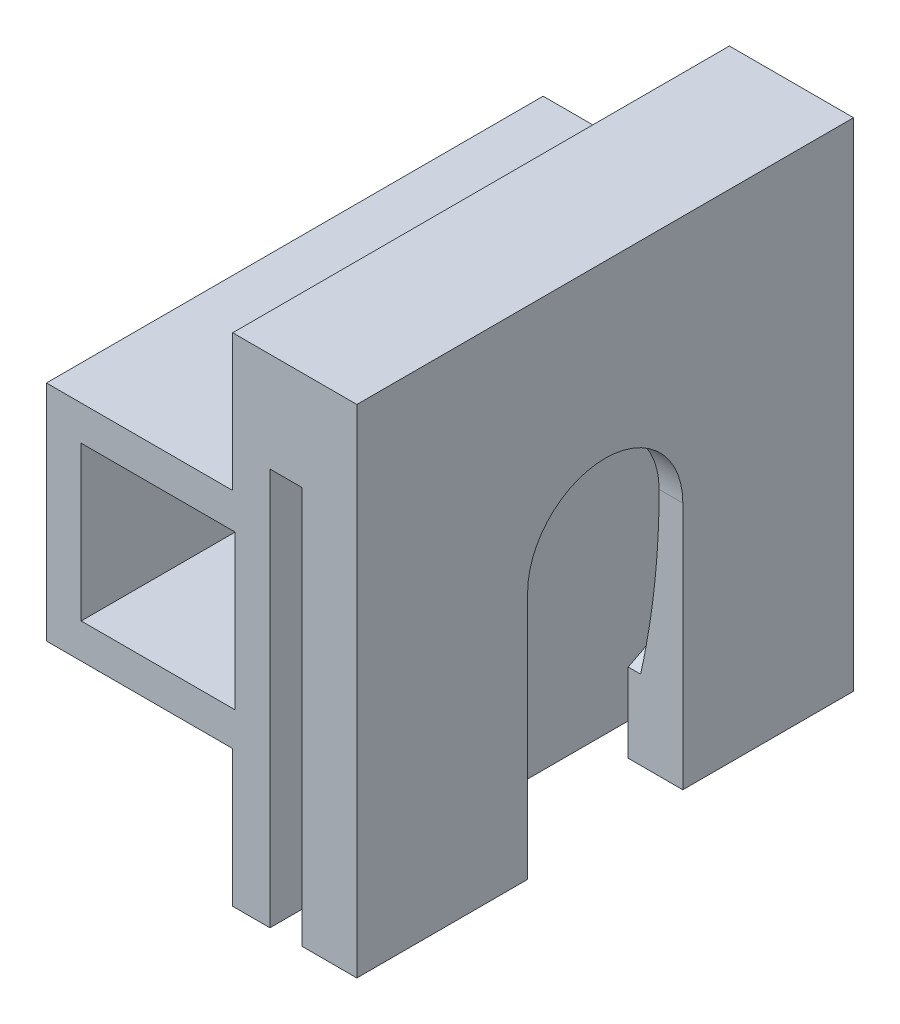
SolidWorks part; units mm, degrees
ref_plane "Plan de face" through (0, 0, 0) normal (0, 0, 1) x (1, 0, 0)
ref_plane "Plan de dessus" through (0, 0, 0) normal (0, 1, 0) x (1, 0, 0)
ref_plane "Plan de droite" through (0, 0, 0) normal (1, 0, 0) x (0, 0, -1)
sketch "Sketch1" plane through (0, 0, 0) normal (0, 0, 1) x (1, 0, 0)
  line L1 (4.5, 4.5) -> (-4.5, 4.5)
  line L2 (4.5, 4.5) -> (4.5, -4.5)
  line L3 (4.5, -4.5) -> (-4.5, -4.5)
  line L4 (-4.5, 4.5) -> (-4.5, -4.5)
  line L5 (4.5, 4.5) -> (-4.5, -4.5) construction
  line L6 (4.5, -4.5) -> (-4.5, 4.5) construction
  point P0 (0, 0)
  dimension "D1" = 9
extrude "Boss-Extrude1" add sketch "Sketch1" along normal blind 20
sketch "Sketch2" plane through (0, 0, 0) normal (0, 0, -1) x (-1, 0, 0)
  line L1 (3, 3) -> (-3, 3)
  line L2 (3, 3) -> (3, -3)
  line L3 (3, -3) -> (-3, -3)
  line L4 (-3, 3) -> (-3, -3)
  line L5 (3, 3) -> (-3, -3) construction
  line L6 (3, -3) -> (-3, 3) construction
  point P0 (0, 0)
  dimension "D1" = 6
extrude "Cut-Extrude1" cut sketch "Sketch2" against normal through all
sketch "Sketch4" plane through (4.5, 0, 0) normal (1, 0, 0) x (0, 0, -1)
  line L0 (-20, -4.5) -> (-20, 4.5) construction
  line L1 (-20, 10) -> (0, 10)
  line L2 (-20, 10) -> (-20, -10)
  line L3 (-20, -10) -> (0, -10)
  line L4 (0, 10) -> (0, -10)
  line L5 (0, -4.5) -> (0, 4.5) construction
  line L6 (-20, 10) -> (0, 4.5) construction
  line L7 (0, -4.5) -> (-20, -10) construction
extrude "Boss-Extrude2" add sketch "Sketch4" against normal up to surface (1.5 mm away) up to face at (3, 0, 10)
ref_plane "Plane1" through (4.5, 0, 0) normal (1, 0, 0) x (0, 0, -1)
ref_plane "Plane2" through (0, 0, 10) normal (0, 0, -1) x (-1, 0, 0)
ref_plane "Plane3" through (0, 0, 0) normal (0, 1, 0) x (1, 0, 0)
ref_axis "Axis1" through (88.99, 0, 10) along (-1, 0, 0)
sketch "Sketch5" plane through (4.5, 0, 0) normal (1, 0, 0) x (0, 0, -1)
  line L4 (0, -10) -> (0, 10)
  line L5 (0, -10) -> (0, 10)
  line L6 (0, 10) -> (-20, 10)
  line L7 (0, 10) -> (-20, 10)
  line L8 (-20, 10) -> (-20, -10)
  line L9 (-20, 10) -> (-20, -10)
  line L10 (-20, -10) -> (0, -10)
  line L11 (-20, -10) -> (0, -10)
  dimension "D1" = 0
extrude "Boss-Extrude3" add sketch "Sketch5" along normal blind 3.5
sketch "Sketch6" plane through (0, 0, 10) normal (0, 0, -1) x (-1, 0, 0)
  line L0 (-4.5, 7.5) -> (-4.5, 0)
  line L1 (-4.5, 0.825) -> (-4.5, -0.825) construction
  line L2 (-4.5, 7.5) -> (-6.3, 7.5)
  line L3 (-6.3, 7.5) -> (-6.3, 0) construction
  line L4 (55, 0) -> (-55, 0) construction
  line L5 (-8, 10) -> (-8, -10) construction
  line L6 (-8, 10) -> (-8, -10) construction
  line L7 (-8, 10) -> (-6.3, 7.5) construction
  line L9 (-4.5, 0) -> (-7.2003, 0)
  arc A0 (-6.3, 7.5) -> (-7.2003, 0) centre (24.49, 0) ccw
  dimension "D3" = 30.79
  dimension "D1" = 1.8
  dimension "D2" = 7.5
revolve "Cut-Revolve2" cut sketch "Sketch6" angle 360 about axis through (88.99, 0, 10) along (-1, 0, 0)
sketch "Sketch7" plane through (0, -10, 0) normal (0, -1, 0) x (1, 0, 0)
  line L0 (3, 20) -> (8, 20) construction
  line L1 (4.5, 20) -> (6.3, 20)
  line L2 (4.5, 20) -> (4.5, 0)
  line L3 (4.5, 0) -> (6.3, 0)
  line L4 (6.3, 20) -> (6.3, 0)
  line L5 (3, 0) -> (8, 0) construction
  line L6 (4.5, 2.5) -> (4.5, 17.5) construction
  line L7 (6.3, 2.5) -> (6.3, 17.5) construction
extrude "Cut-Extrude5" cut sketch "Sketch7" against normal blind 16
sketch "Sketch8" plane through (8, 0, 0) normal (1, 0, 0) x (0, 0, -1)
  line L0 (-10, 0) -> (-10, -10) construction
  line L1 (-6.875, 0) -> (-6.875, -10)
  line L2 (-13.125, 0) -> (-13.125, -10)
  line L3 (-10, -0.825) -> (-10, 0.825) construction
  line L4 (55, 0) -> (-55, 0) construction
  line L5 (-20, -10) -> (0, -10) construction
  arc A0 (-6.875, 0) -> (-13.125, 0) centre (-10, 0) ccw
  arc A1 (-13.125, -10) -> (-6.875, -10) centre (-10, -10) ccw
  point P2 (-10, -5)
  dimension "D1" = 6.25
extrude "Cut-Extrude6" cut sketch "Sketch8" against normal up to surface (1.7 mm away)
sketch "Sketch9" plane through (6.3, 0, 0) normal (-1, 0, 0) x (0, 0, 1)
  line L0 (13.125, -6.8179) -> (13.125, -10) construction
  line L1 (13.125, -10) -> (20, -10) construction
  line L2 (20, -10) -> (20, 6) construction
  line L3 (20, 6) -> (14.5, 6) construction
  line L4 (0, -10) -> (6.875, -10) construction
  line L5 (6.875, -10) -> (6.875, -6.8179) construction
  line L6 (5.5, 6) -> (0, 6) construction
  line L7 (0, 6) -> (0, -10) construction
  line L8 (13.125, -6.8179) -> (13.125, -10)
  line L9 (13.125, -10) -> (20, -10)
  line L10 (20, -10) -> (20, 6)
  line L11 (20, 6) -> (14.5, 6)
  line L12 (0, -10) -> (6.875, -10)
  line L13 (6.875, -10) -> (6.875, -6.8179)
  line L14 (5.5, 6) -> (0, 6)
  line L15 (0, 6) -> (0, -10)
  arc A0 (13.125, -6.8179) -> (14.5, 6) centre (10, 0) ccw construction
  arc A1 (5.5, 6) -> (6.875, -6.8179) centre (10, 0) ccw construction
  arc A2 (13.125, -6.8179) -> (14.5, 6) centre (10, 0) ccw
  arc A3 (5.5, 6) -> (6.875, -6.8179) centre (10, 0) ccw
extrude "Boss-Extrude4" add sketch "Sketch9" along normal blind 0.5
sketch "Sketch10" plane through (0, 0, 0) normal (0, 0, -1) x (-1, 0, 0)
  line L0 (3, 3) -> (-3, 3) construction
  line L1 (3.1, -3.1) -> (-3.1, -3.1)
  line L2 (3.1, -3.1) -> (3.1, 3.1)
  line L3 (3.1, 3.1) -> (-3.1, 3.1)
  line L4 (-3.1, -3.1) -> (-3.1, 3.1)
  line L5 (3.1, -3.1) -> (-3.1, 3.1) construction
  line L6 (3.1, 3.1) -> (-3.1, -3.1) construction
  point P0 (0, 0)
  dimension "D1" = 0.1
extrude "Cut-Extrude8" cut sketch "Sketch10" against normal through all
